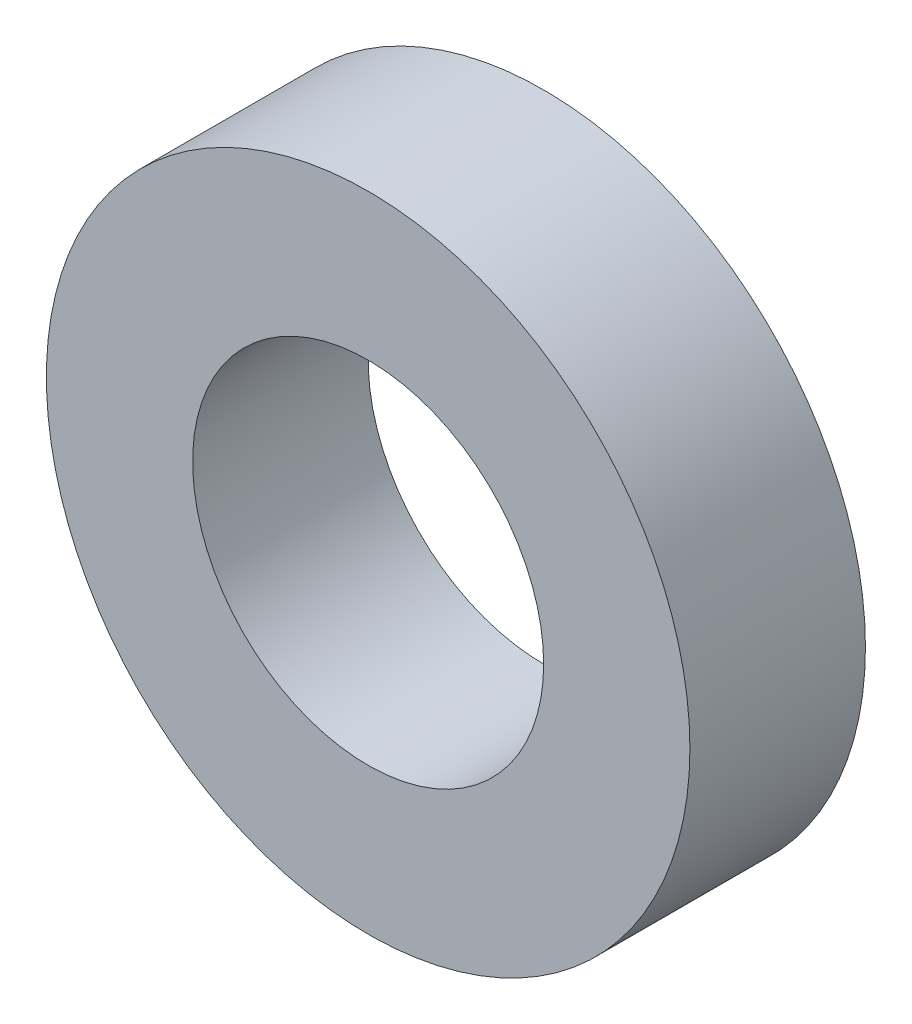
SolidWorks part; units mm, degrees
ref_plane "Alzado" through (0, 0, 0) normal (0, 0, 1) x (1, 0, 0)
ref_plane "Planta" through (0, 0, 0) normal (0, 1, 0) x (1, 0, 0)
ref_plane "Vista lateral" through (0, 0, 0) normal (1, 0, 0) x (0, 0, -1)
sketch "Croquis1" plane through (0, 0, 0) normal (0, 0, 1) x (1, 0, 0)
  circle A0 centre (0, 0) radius 3
  circle A1 centre (0, 0) radius 5.5
  dimension "D1" = 6
  dimension "D2" = 11
extrude "Saliente-Extruir1" add sketch "Croquis1" along normal blind 3
